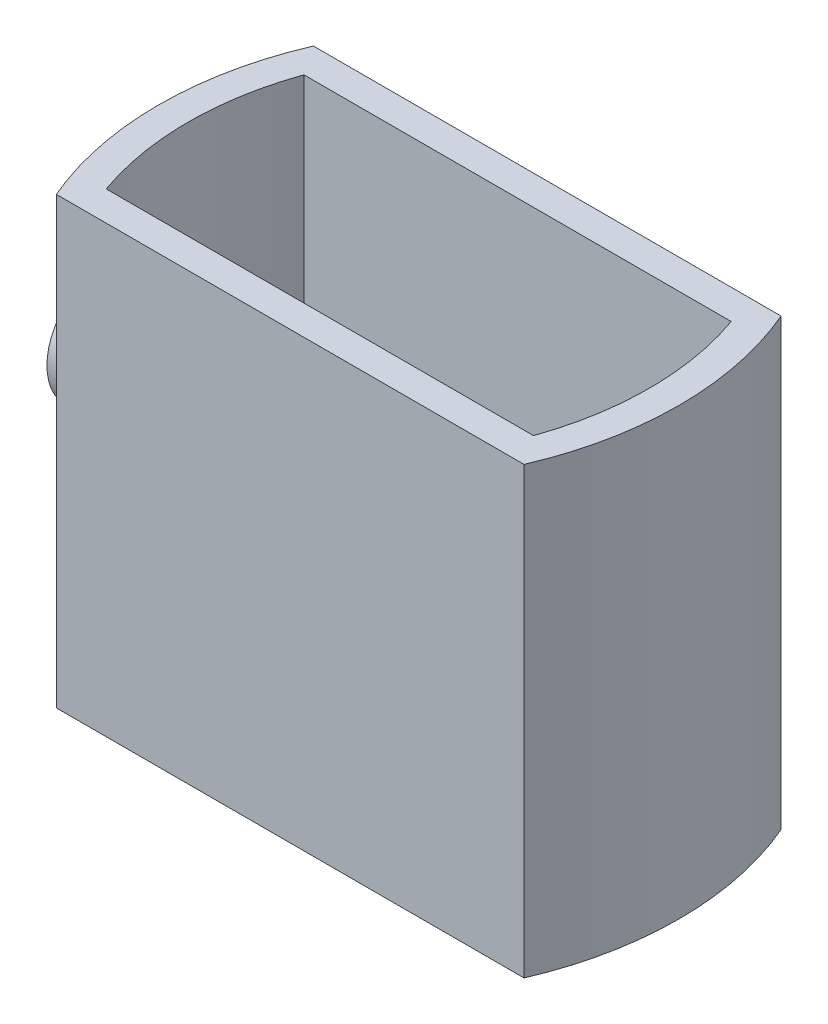
SolidWorks part; units mm, degrees
material "PET"
ref_plane "Alzado" through (0, 0, 0) normal (0, 0, 1) x (1, 0, 0)
ref_plane "Planta" through (0, 0, 0) normal (0, 1, 0) x (1, 0, 0)
ref_plane "Vista lateral" through (0, 0, 0) normal (1, 0, 0) x (0, 0, -1)
sketch "Croquis1" plane through (0, 0, 0) normal (0, 1, 0) x (1, 0, 0)
  line L0 (26.6143, 20) -> (26.6143, 0) construction
  line L1 (5, 0) -> (48.2285, 0)
  line L3 (5, 20) -> (48.2285, 20)
  line L5 (2.9528, -3) -> (50.2758, -3)
  line L6 (2.9528, 23) -> (50.2758, 23)
  arc A0 (5, 20) -> (5, 0) centre (33.2843, 10) ccw
  arc A1 (48.2285, 20) -> (48.2285, 0) centre (19.9443, 10) cw
  arc A2 (2.9528, 23) -> (2.9528, -3) centre (33.2843, 10) ccw
  arc A3 (50.2758, 23) -> (50.2758, -3) centre (19.9443, 10) cw
  point P14 (26.6143, 10)
  point P19 (3.2843, 10)
  dimension "D3" = 30
  dimension "D1" = 23.33
  dimension "D2" = 3
  dimension "D4" = 20
extrude "Saliente-Extruir1" add sketch "Croquis1" along normal blind 45
sketch "Croquis2" plane through (0, 0, 0) normal (0, -1, 0) x (1, 0, 0)
  line L0 (2.9528, 3) -> (50.2758, 3)
  line L1 (2.9528, -23) -> (50.2758, -23)
  line L2 (26.6143, 3) -> (26.6143, -23) construction
  line L3 (15.1143, -20) -> (38.1143, -20)
  line L4 (38.1143, 0) -> (15.1143, 0)
  line L5 (5, 0) -> (48.2285, 0) construction
  arc A0 (2.9528, 3) -> (2.9528, -23) centre (33.2843, -10) ccw
  arc A1 (50.2758, 3) -> (50.2758, -23) centre (19.9443, -10) cw
  arc A4 (15.1143, 0) -> (15.1143, -20) centre (43.3985, -10) ccw
  arc A5 (38.1143, 0) -> (38.1143, -20) centre (0.17, -10) cw
  dimension "D2" = 43.2285
  dimension "D1" = 20
  dimension "D3" = 23
extrude "Saliente-Extruir2" add sketch "Croquis2" against normal blind 3
sketch "Croquis3" plane through (0, 0, 0) normal (1, 0, 0) x (0, 0, -1)
  line L0 (10, 0) -> (10, 32.4501) construction
  line L1 (-3, 0) -> (23, 0) construction
  circle A0 centre (10, 22.5299) radius 6
  dimension "D1" = 12
extrude "Saliente-Extruir3" add sketch "Croquis3" along normal up to surface (0.8343 mm away)
sketch "Croquis4" plane through (0, 0, 0) normal (-1, 0, 0) x (0, 0, 1)
  circle A0 centre (-10, 22.5299) radius 6
extrude "Saliente-Extruir4" add sketch "Croquis4" along normal blind 5
sketch "Croquis5" plane through (-5, 0, 0) normal (-1, 0, 0) x (0, 0, 1)
  circle A0 centre (-10, 22.5299) radius 3
  dimension "D1" = 6
extrude "Cortar-Extruir1" cut sketch "Croquis5" against normal blind 12
